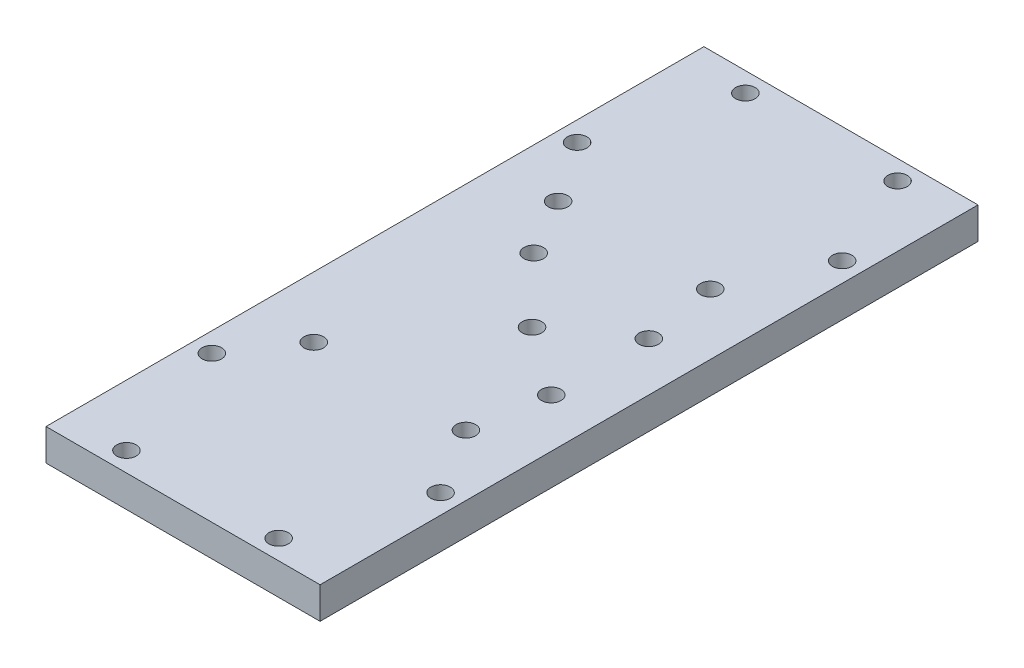
SolidWorks part; units mm, degrees
material "PBT General Purpose"
ref_plane "Front Plane" through (0, 0, 0) normal (0, 0, 1) x (1, 0, 0)
ref_plane "Top Plane" through (0, 0, 0) normal (0, 1, 0) x (1, 0, 0)
ref_plane "Right Plane" through (0, 0, 0) normal (1, 0, 0) x (0, 0, -1)
sketch "Sketch1" plane through (0, 0, 0) normal (0, 1, 0) x (1, 0, 0)
  line L0 (-52.2, 30) -> (-4, 30) construction
  line L1 (-4, 30) -> (-4, 28.7) construction
  line L2 (-52.2, 104.9) -> (-52.2, 30) construction
  line L3 (-4, 111.05) -> (-4, 28.7) construction
  line L5 (-56.2, 134.9) -> (0, 134.9)
  line L6 (-56.2, 134.9) -> (-56.2, 0)
  line L7 (-56.2, 0) -> (0, 0)
  line L8 (0, 134.9) -> (0, 0)
  circle A0 centre (-52.2, 104.9) radius 2
  circle A1 centre (-4, 111.05) radius 2
  circle A2 centre (-37, 80.8) radius 2
  circle A4 centre (-52.2, 30) radius 2
  circle A5 centre (-4, 28.7) radius 2
  dimension "D1" = 4
  dimension "D2" = 48.2
  dimension "D3" = 1.3
  dimension "D4" = 82.35
  dimension "D5" = 74.9
  dimension "D7" = 15.2
  dimension "D9" = 30
  dimension "D10" = 30
  dimension "D11" = 4
  dimension "D12" = 4
extrude "Boss-Extrude1" add sketch "Sketch1" along normal blind 6.5
sketch "Pololu Mounting Bracket" plane through (0, 6.5, 0) normal (0, 1, 0) x (1, 0, 0)
  line L0 (-56.2, 0) -> (0, 0) construction
  line L2 (0, 134.9) -> (-56.2, 134.9) construction
  circle A0 centre (-43.7, 4) radius 2
  circle A1 centre (-12.5, 4) radius 2
  circle A2 centre (-43.7, 42.4) radius 2
  circle A3 centre (-12.5, 42.4) radius 2
  circle A4 centre (-43.7, 130.9) radius 2
  circle A5 centre (-12.5, 130.9) radius 2
  circle A6 centre (-12.5, 92.5) radius 2
  circle A7 centre (-43.7, 92.5) radius 2
  point P4 (-28.1, 0)
  point P7 (-28.1, 134.9)
  dimension "D1" = 4
  dimension "D2" = 31.2
  dimension "D4" = 4
  dimension "D5" = 38.4
  dimension "D6" = 15.6
  dimension "D3" = 15.6
  dimension "D7" = 31.2
  dimension "D8" = 38.4
  dimension "D9" = 31.2
extrude "Pololu 37mm mounting bracket holes" cut sketch "Pololu Mounting Bracket" against normal through all
sketch "Sketch2" plane through (0, 0, 0) normal (0, -1, 0) x (1, 0, 0)
  line L0 (0, 0) -> (0, -134.9) construction
  circle A0 centre (-24, -67.45) radius 2
  circle A1 centre (-10, -77.3953) radius 2
  circle A2 centre (-10, -57.3953) radius 2
  point P2 (0, -67.45)
  dimension "D1" = 4
  dimension "D2" = 20
  dimension "D3" = 14
  dimension "D4" = 10
extrude "Spindle Mount" cut sketch "Sketch2" against normal through all
